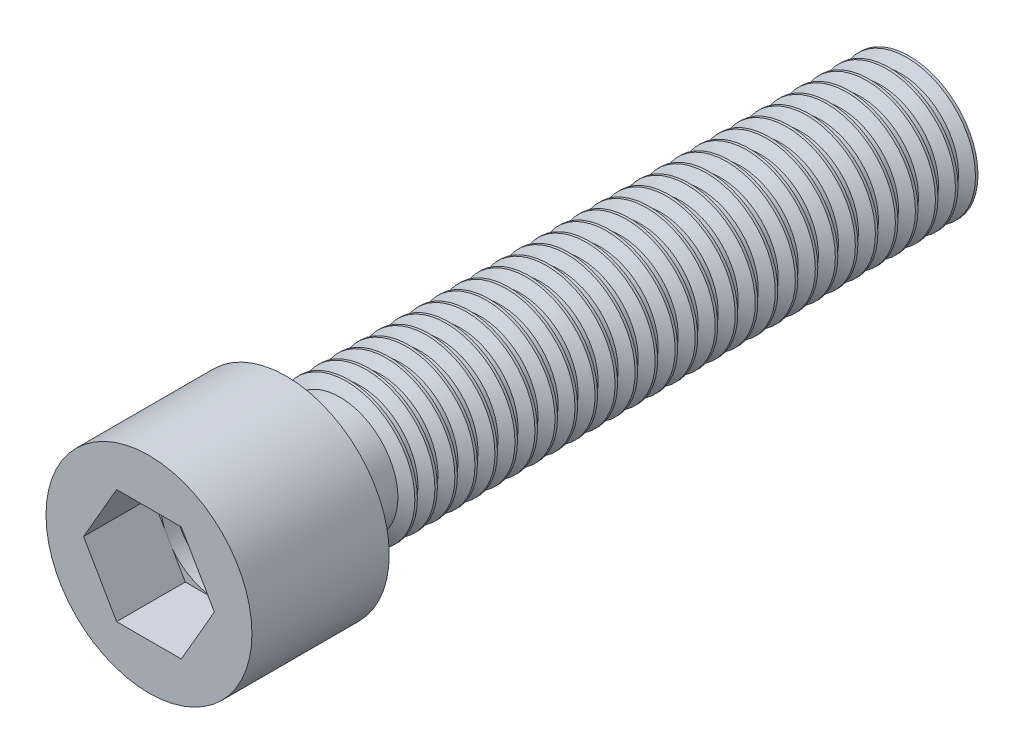
SolidWorks part; units mm, degrees
ref_plane "Plane1" through (0, 0, 0) normal (0, 0, 1) x (1, 0, 0)
ref_plane "Plane2" through (0, 0, 0) normal (0, 1, 0) x (1, 0, 0)
ref_plane "Plane3" through (0, 0, 0) normal (1, 0, 0) x (0, 0, -1)
sketch "Sketch1" plane through (0, 0, 0) normal (0, 0, 1) x (1, 0, 0)
  circle A0 centre (0, 0) radius 5.0594
  dimension "D1" = 10.1188
extrude "Base-Extrude" add sketch "Sketch1" along normal blind 55
sketch "Sketch2" plane through (0, 0, 0) normal (0, 1, 0) x (1, 0, 0)
  line L0 (5.0594, 0) -> (6, -0.5431)
  line L1 (5.0594, 0) -> (-5.0594, 0) construction
  line L2 (6, -0.5431) -> (6, -0.7618)
  line L4 (6, -0.7618) -> (5.0594, -1.3049)
  line L5 (5.0594, -55) -> (5.0594, 0) construction
  line L6 (5.0594, 0) -> (5.0594, -1.3049)
  dimension "D1" = 60
  dimension "D2" = 6
  dimension "D3" = 0.2188
  dimension "D4" = 5.0594
  dimension "D9" = 60
ref_plane "Plane5" through (0, 0, 0.5) normal (0, 0, -1) x (-1, 0, 0)
sketch "Sketch4" plane through (0, 0, 0.5) normal (0, 0, -1) x (-1, 0, 0)
  circle A0 centre (0, 0) radius 5.0594 construction
  circle A1 centre (0, 0) radius 5.0594
sweep "Boss-Sweep1" add profiles "Sketch2" path "Sketch4"
sketch "Sketch5" plane through (0, 0, 0) normal (0, 1, 0) x (1, 0, 0)
  line L0 (0, 0) -> (0, -1.4038)
  line L2 (0, -0.5431) -> (0, 0) construction
pattern_linear "LPattern1" count 29 spacing 1.75 along (0, 0, 1) of "Boss-Sweep1"
sketch "Sketch7" plane through (0, 0, 0) normal (0, 1, 0) x (1, 0, 0)
  line L0 (0, 0) -> (0, -22.3053) construction
  line L1 (0, -21) -> (0, -20.5549) construction
  line L2 (0, -55) -> (9, -55)
  line L3 (9, -55) -> (9, -67)
  line L5 (9, -67) -> (0, -67)
  line L6 (0, -67) -> (0, -55)
  dimension "D13" = 12
  dimension "D12" = 9
  dimension "D14" = 55
revolve "Boss-Revolve2" add sketch "Sketch7" angle 360 about L0
sketch "Sketch8" plane through (0, 0, 67) normal (0, 0, 1) x (1, 0, 0)
  line L0 (-5, 0) -> (5, 0) construction
  line L1 (0, 6.1) -> (0, -5.8) construction
  line L4 (-2.8282, 5) -> (2.8282, 5)
  line L5 (2.8282, 5) -> (5.715, 0)
  line L6 (-2.8282, 5) -> (-5.715, 0)
  line L7 (2.8282, -5) -> (5.715, 0)
  line L8 (-2.8282, -5) -> (2.8282, -5)
  line L9 (-2.8282, -5) -> (-5.715, 0)
  dimension "D1" = 5.715
  dimension "D2" = 60
  dimension "D16" = 11.43
  dimension "D15" = 10
extrude "Cut-Extrude2" cut sketch "Sketch8" against normal blind 6
sketch "Sketch9" plane through (0, 0, 0) normal (0, 1, 0) x (1, 0, 0)
  line L0 (0, 0) -> (0, -35.025) construction
  line L1 (0, -0.7618) -> (0, -1.3049) construction
  line L2 (0, -61) -> (5, -61)
  line L3 (5, -61) -> (5, -59.8)
  line L4 (5, -59.8) -> (0, -58.4603)
  line L5 (0, -58.4603) -> (0, -61)
  dimension "D1" = 15
  dimension "D18" = 5
  dimension "D19" = 1.2
  dimension "D20" = 61
revolve "Cut-Revolve1" cut sketch "Sketch9" angle 360 about L0
